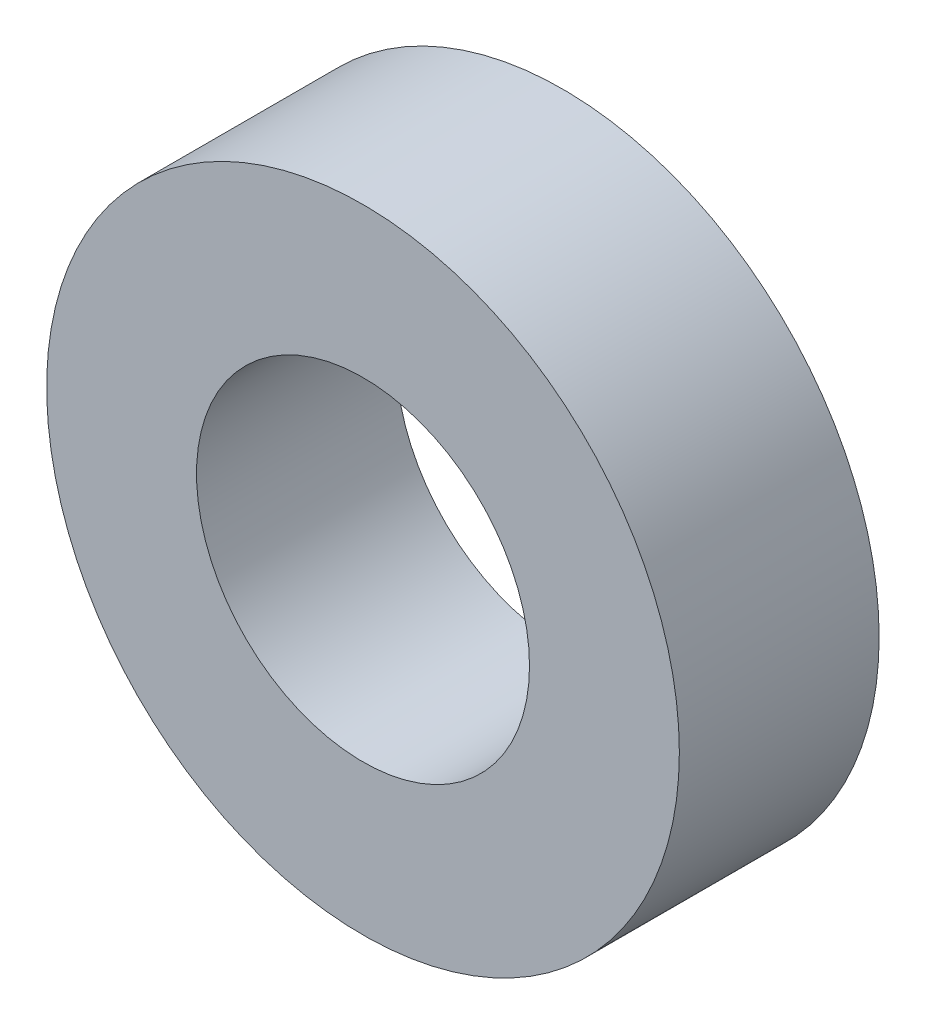
SolidWorks part; units mm, degrees
ref_plane "正面" through (0, 0, 0) normal (0, 0, 1) x (1, 0, 0)
ref_plane "平面" through (0, 0, 0) normal (0, 1, 0) x (1, 0, 0)
ref_plane "右側面" through (0, 0, 0) normal (1, 0, 0) x (0, 0, -1)
sketch "ｽｹｯﾁ1" plane through (0, 0, 0) normal (0, 0, 1) x (1, 0, 0)
  circle A0 centre (0, 0) radius 5
  dimension "D1" = 10
extrude "押し出し-薄板1" add sketch "ｽｹｯﾁ1" along normal mid plane 6 thin
